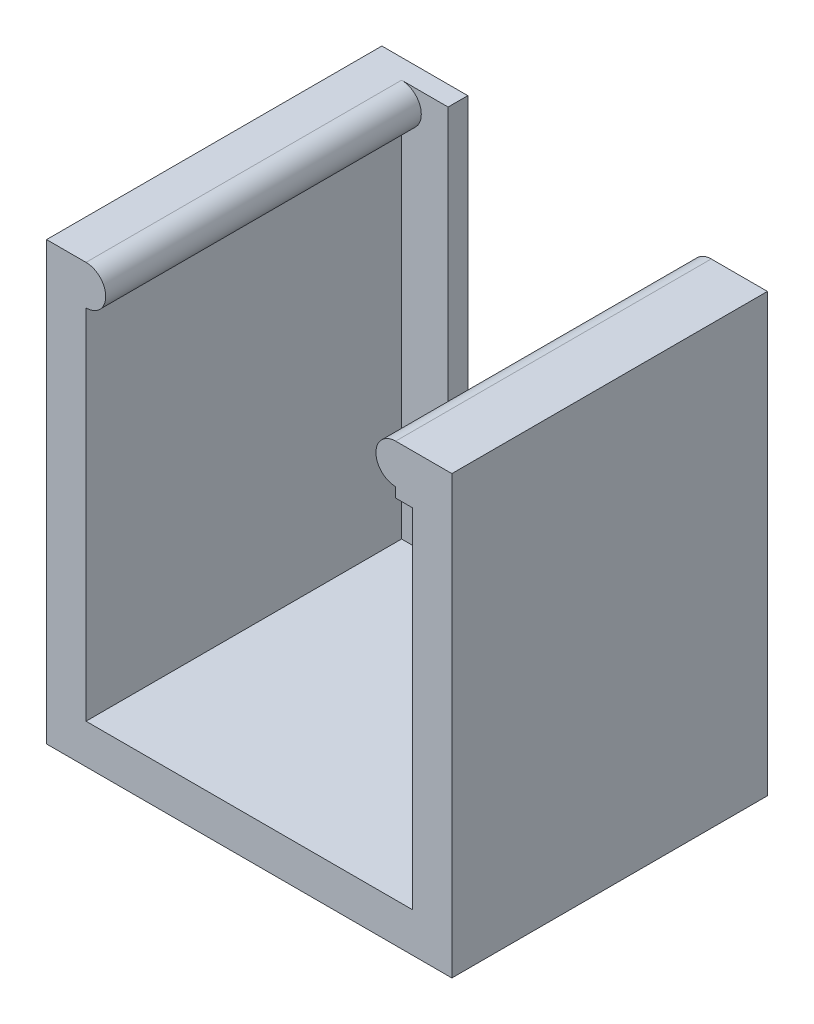
SolidWorks part; units mm, degrees
ref_plane "Front Plane" through (0, 0, 0) normal (0, 0, 1) x (1, 0, 0)
ref_plane "Top Plane" through (0, 0, 0) normal (0, 1, 0) x (1, 0, 0)
ref_plane "Right Plane" through (0, 0, 0) normal (1, 0, 0) x (0, 0, -1)
sketch "Sketch1" plane through (0, 0, 0) normal (0, 0, 1) x (1, 0, 0)
  line L0 (0, 0) -> (0, 5.6021) construction
  line L1 (-7.85, 0) -> (7.85, 0) construction
  circle A0 centre (-7.85, 0) radius 1
  circle A1 centre (7.85, 0) radius 1
  point P7 (0, 0)
  dimension "D1" = 2
  dimension "D2" = 15.7
extrude "Boss-Extrude1" add sketch "Sketch1" along normal blind 16
sketch "Sketch2" plane through (0, 0, 0) normal (0, 0, 1) x (1, 0, 0)
  line L0 (7.85, 1) -> (10.7, 1)
  line L1 (10.7, 1) -> (10.7, -21.1488)
  line L2 (-7.85, 1) -> (-9.85, 1)
  line L3 (-9.85, 1) -> (-9.85, -21.1488)
  line L4 (7.85, 1) -> (7.85, -1.5)
  line L5 (7.85, -1.5) -> (8.7, -1.5)
  line L6 (8.7, -1.5) -> (8.7, -19.1488)
  line L7 (-7.85, 1) -> (-7.85, -19.1488)
  line L8 (-7.85, -19.1488) -> (8.7, -19.1488)
  line L9 (10.7, -21.1488) -> (-9.85, -21.1488)
  circle A0 centre (7.85, 0) radius 1 construction
  circle A1 centre (-7.85, 0) radius 1 construction
  dimension "D1" = 2
  dimension "D2" = 2
  dimension "D3" = 2
  dimension "D4" = 0.85
  dimension "D5" = 2.5
extrude "Boss-Extrude2" add sketch "Sketch2" along normal through all
sketch "Sketch3" plane through (0, 0, 0) normal (0, 0, 1) x (1, 0, 0)
  line L1 (-9.85, 1) -> (-5.4919, 1)
  line L2 (-9.85, 1) -> (-9.85, -20.3611)
  line L3 (-9.85, -20.3611) -> (-5.4919, -20.3611)
  line L4 (-5.4919, 1) -> (-5.4919, -20.3611)
extrude "Boss-Extrude4" add sketch "Sketch3" against normal blind 1 contours L4 L3 L2 L1
